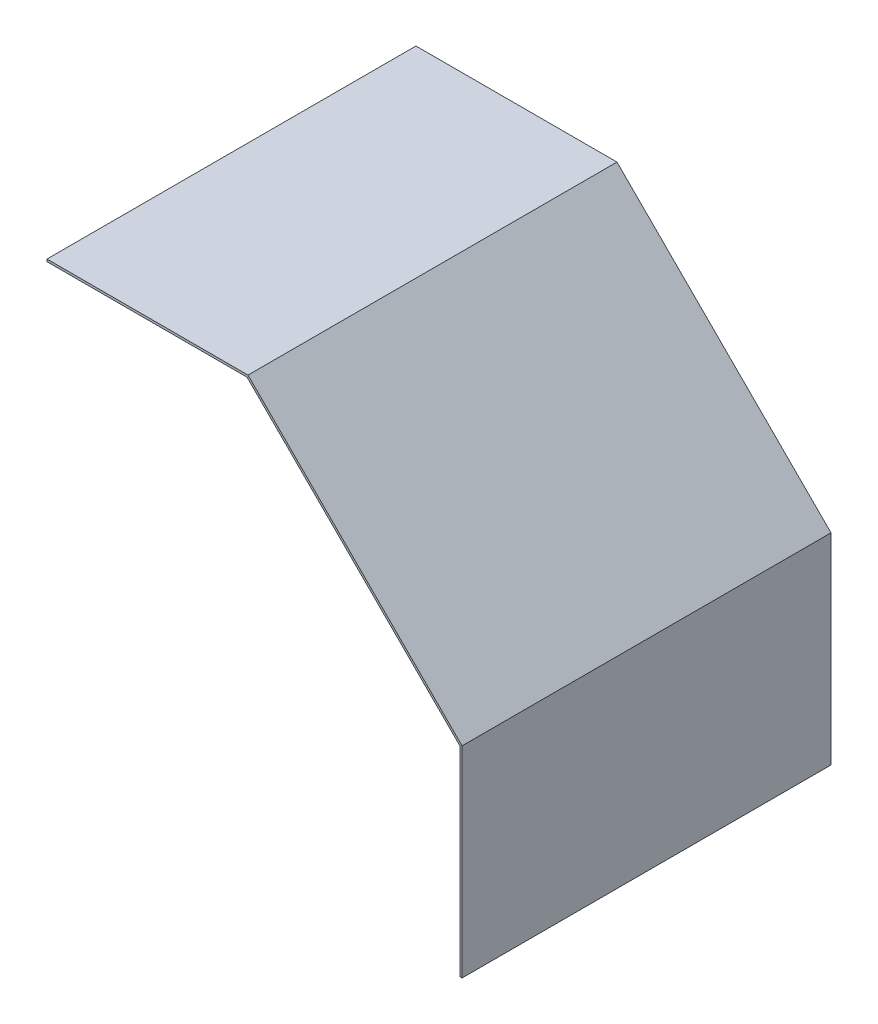
SolidWorks part; units mm, degrees
ref_plane "Front Plane" through (0, 0, 0) normal (0, 0, 1) x (1, 0, 0)
ref_plane "Top Plane" through (0, 0, 0) normal (0, 1, 0) x (1, 0, 0)
ref_plane "Right Plane" through (0, 0, 0) normal (1, 0, 0) x (0, 0, -1)
sketch "Sketch1" plane through (0, 0, 0) normal (0, 0, 1) x (1, 0, 0)
  line L0 (45, 21.7945) -> (45, 0) construction
  line L1 (21.7945, 45) -> (45, 21.7945) construction
  line L2 (0, 45) -> (21.7945, 45) construction
  line L3 (45, 21.7945) -> (45, 0)
  line L4 (21.7945, 45) -> (45, 21.7945)
  line L5 (0, 45) -> (21.7945, 45)
extrude "Extrude-Thin1" add sketch "Sketch1" along normal blind 40 thin
